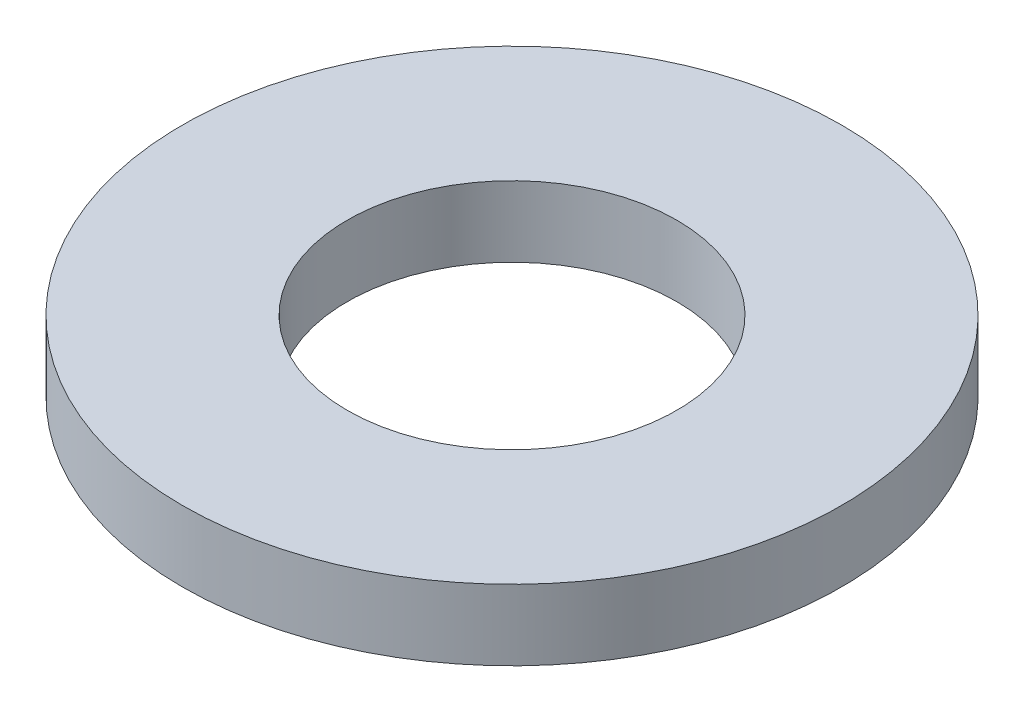
SolidWorks part; units mm, degrees
ref_plane "Front Plane" through (0, 0, 0) normal (0, 0, 1) x (1, 0, 0)
ref_plane "Top Plane" through (0, 0, 0) normal (0, 1, 0) x (1, 0, 0)
ref_plane "Right Plane" through (0, 0, 0) normal (1, 0, 0) x (0, 0, -1)
sketch "Sketch1" plane through (0, 0, 0) normal (0, 1, 0) x (1, 0, 0)
  circle A0 centre (0, 0) radius 14
  circle A1 centre (0, 0) radius 7
  dimension "D1" = 14
  dimension "D2" = 28
extrude "Boss-Extrude1" add sketch "Sketch1" along normal mid plane 3
